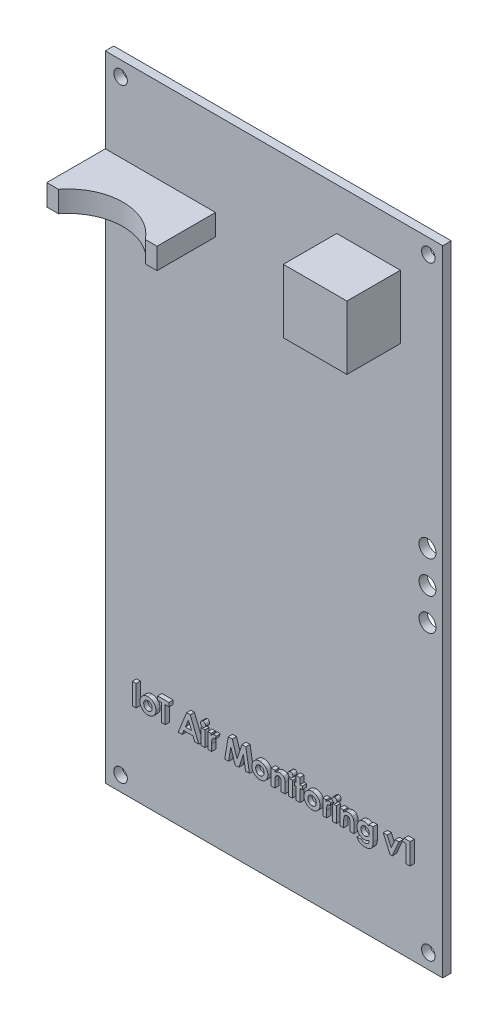
SolidWorks part; units mm, degrees
material "ABS"
ref_plane "Přední rovina" through (0, 0, 0) normal (0, 0, 1) x (1, 0, 0)
ref_plane "Horní rovina" through (0, 0, 0) normal (0, 1, 0) x (1, 0, 0)
ref_plane "Pravá rovina" through (0, 0, 0) normal (1, 0, 0) x (0, 0, -1)
sketch "Skica1" plane through (0, 0, 0) normal (0, 0, 1) x (1, 0, 0)
  line L0 (72.5, 7.2) -> (79.9, -0.2) construction
  line L1 (0, 0) -> (79.6, 0)
  line L2 (0, 0) -> (0, 149.6)
  line L3 (0, 149.6) -> (79.6, 149.6)
  line L4 (79.6, 0) -> (79.6, 149.6)
  line L5 (-0.1, 149.8) -> (79.9, 149.8) construction
  line L6 (-0.1, 149.8) -> (-0.1, -0.2) construction
  line L7 (-0.1, -0.2) -> (79.9, -0.2) construction
  line L8 (79.9, 149.8) -> (79.9, -0.2) construction
  line L9 (-0.1, -0.2) -> (7.3, -0.2) construction
  line L10 (-0.1, -0.2) -> (-0.1, 7.2) construction
  line L11 (-0.1, 7.2) -> (7.3, 7.2) construction
  line L12 (7.3, -0.2) -> (7.3, 7.2) construction
  line L13 (79.9, -0.2) -> (72.5, -0.2) construction
  line L14 (79.9, -0.2) -> (79.9, 7.2) construction
  line L15 (79.9, 7.2) -> (72.5, 7.2) construction
  line L16 (72.5, -0.2) -> (72.5, 7.2) construction
  line L17 (7.3, 7.2) -> (-0.1, -0.2) construction
  line L18 (61.69, -4.5018) -> (61.7914, -4.4005) construction
  line L19 (-0.1, 149.8) -> (7.3, 142.4) construction
  line L20 (-0.1, 149.8) -> (7.3, 149.8) construction
  line L21 (-0.1, 149.8) -> (-0.1, 142.4) construction
  line L22 (-0.1, 142.4) -> (7.3, 142.4) construction
  line L23 (7.3, 149.8) -> (7.3, 142.4) construction
  line L24 (79.9, 149.8) -> (72.5, 142.4) construction
  line L25 (79.9, 149.8) -> (72.5, 149.8) construction
  line L26 (79.9, 149.8) -> (79.9, 142.4) construction
  line L27 (79.9, 142.4) -> (72.5, 142.4) construction
  line L28 (72.5, 149.8) -> (72.5, 142.4) construction
  circle A0 centre (3.6, 3.5) radius 1.6
  circle A1 centre (76.2, 3.5) radius 1.6
  circle A2 centre (3.6, 146.1) radius 1.6
  circle A3 centre (76.2, 146.1) radius 1.6
  dimension "D11" = 3.2
  dimension "D14" = 3.2
  dimension "D15" = 3.2
  dimension "D18" = 3.2
  dimension "D1" = 79.6
  dimension "D2" = 149.6
  dimension "D3" = 0.2
  dimension "D4" = 80
  dimension "D5" = 0.2
  dimension "D6" = 150
  dimension "D7" = 7.4
  dimension "D8" = 7.4
  dimension "D9" = 7.4
  dimension "D10" = 7.4
  dimension "D12" = 7.4
  dimension "D13" = 7.4
  dimension "D16" = 7.4
  dimension "D17" = 7.4
extrude "Přidat vysunutím1" add sketch "Skica1" along normal blind 2
sketch "Skica2" plane through (0, 0, 2) normal (0, 0, 1) x (1, 0, 0)
  line L0 (0, 149.6) -> (0, 0) construction
  line L1 (0, 129.6) -> (26, 129.6)
  line L2 (0, 129.6) -> (0, 124.6)
  line L3 (0, 124.6) -> (26, 124.6)
  line L4 (26, 129.6) -> (26, 124.6)
  line L5 (79.6, 149.6) -> (0, 149.6) construction
  dimension "D1" = 5
  dimension "D2" = 20
  dimension "D3" = 26
extrude "Přidat vysunutím2" add sketch "Skica2" along normal blind 8.8
sketch "Skica3" plane through (0, 124.6, 0) normal (0, -1, 0) x (1, 0, 0)
  line L1 (0, 10.8) -> (26, 10.8) construction
  line L2 (0, 10.8) -> (26, 10.8)
  line L3 (26, 10.8) -> (26, 15.8)
  line L4 (26, 15.8) -> (23.247, 15.8)
  line L5 (0, 10.8) -> (0, 15.8)
  line L6 (0, 15.8) -> (2.753, 15.8)
  arc A0 (2.753, 15.8) -> (23.247, 15.8) centre (13, 23.8) ccw
  point P5 (13, 10.8)
  point P11 (23.247, 16)
  line M7 (26, 10.8) -> (0, 10.8)
  dimension "D1" = 26
  dimension "D2" = 5
  dimension "D3" = 5
extrude "Přidat vysunutím3" add sketch "Skica3" against normal up to surface (5 mm away) contours A0 L6 L5 L2 | A0 L3 L4 M7 up to face at (13, 129.6, 6.4)
sketch "Skica4" plane through (0, 0, 2) normal (0, 0, 1) x (1, 0, 0)
  line L0 (79.6, 149.6) -> (0, 149.6) construction
  line L1 (54.6, 139.6) -> (69.6, 139.6)
  line L2 (54.6, 139.6) -> (54.6, 124.6)
  line L3 (54.6, 124.6) -> (69.6, 124.6)
  line L4 (69.6, 139.6) -> (69.6, 124.6)
  line L5 (79.6, 0) -> (79.6, 149.6) construction
  dimension "D1" = 15
  dimension "D2" = 15
  dimension "D3" = 10
  dimension "D4" = 10
extrude "Přidat vysunutím4" add sketch "Skica4" along normal blind 12.6
sketch "Skica5" plane through (0, 0, 2) normal (0, 0, 1) x (1, 0, 0)
  line L0 (76, 104.154) -> (76, 5.3798) construction
  line L1 (79.6, 0) -> (79.6, 149.6) construction
  line L2 (0, 0) -> (79.6, 0) construction
  circle A0 centre (76, 86) radius 2
  circle A1 centre (76, 78.4) radius 2
  circle A2 centre (76, 70.8) radius 2
  point P10 (0, 0)
  point P11 (0, 0)
  point P12 (0, 0)
  point P13 (0, 0)
  dimension "D5" = 4
  dimension "D1" = 3.6
  dimension "D2" = 86
  dimension "D3" = 78.4
  dimension "D4" = 70.8
extrude "Odebrat vysunutím1" cut sketch "Skica5" against normal through all
sketch "Skica6" plane through (0, 0, 0) normal (0, 0, -1) x (-1, 0, 0)
  line L0 (-76, 84) -> (-53.4794, 84) construction
  line L1 (-76, 76.4) -> (-53.4794, 76.4) construction
  line L4 (-76, 68.8) -> (-53.4794, 68.8) construction
  circle A0 centre (-76, 86) radius 2 construction
  circle A1 centre (-76, 78.4) radius 2 construction
  circle A2 centre (-76, 70.8) radius 2 construction
  text T0 "<b>    RST</b>" font "@Adobe Heiti Std R" height 4
  text T1 "<b>    OFF</b>" font "@Adobe Heiti Std R" height 4
  text T2 "<b>    ON</b>" font "@Adobe Heiti Std R" height 4
  point P14 (0, 0)
  point P15 (0, 0)
extrude "Odebrat vysunutím2" cut sketch "Skica6" against normal blind 0.6
sketch "Skica7" plane through (0, 0, 2) normal (0, 0, 1) x (1, 0, 0)
  line L0 (0, 124.6) -> (0, 0) construction
  line L1 (0, 0) -> (79.6, 0) construction
  line L2 (5, 20) -> (74.6, 20) construction
  line L4 (79.6, 0) -> (79.6, 149.6) construction
  text T0 "<b> IoT Air Monitoring v1</b>" font "Century Gothic" height 5
  point P4 (7.8027, 20)
  point P6 (73.3276, 20)
  dimension "D1" = 20
  dimension "D2" = 5
  dimension "D3" = 5
extrude "Přidat vysunutím5" add sketch "Skica7" along normal blind 1
